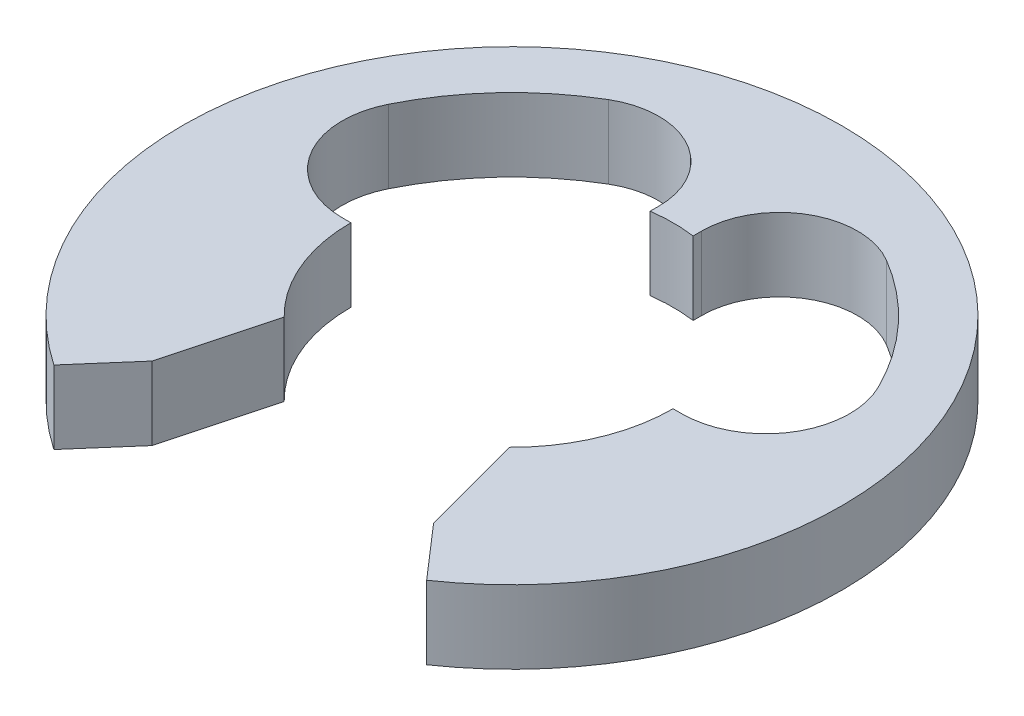
SolidWorks part; units mm, degrees
ref_plane "Plane1" through (0, 0, 0) normal (0, 0, 1) x (1, 0, 0)
ref_plane "Plane2" through (0, 0, 0) normal (0, 1, 0) x (1, 0, 0)
ref_plane "Plane3" through (0, 0, 0) normal (1, 0, 0) x (0, 0, -1)
extrude "Base-Extrude" add sketch "Sketch1" against normal blind 0.5
sketch "Sketch1" plane through (0, 0, 0) normal (0, 1, 0) x (1, 0, 0)
  line L0 (0, 0) -> (0, 100) construction
  line L1 (0.77, -0.7856) -> (0.9604, -1.4961)
  line L2 (0.9604, -1.4961) -> (1.2728, -1.8554)
  line L3 (0.1467, 1.0902) -> (0.1467, 1.1488)
  line L4 (1.1, 0) -> (1.1587, 0)
  line L5 (-1.1, 0) -> (-1.1587, 0)
  line L6 (-0.1467, 1.0902) -> (-0.1467, 1.1488)
  line L7 (-0.9604, -1.4961) -> (-1.2728, -1.8554)
  line L8 (-0.77, -0.7856) -> (-0.9604, -1.4961)
  arc A0 (1.2728, -1.8554) -> (-1.2728, -1.8554) centre (0, 0) ccw
  arc A1 (0.1467, 1.0902) -> (-0.1467, 1.0902) centre (0, 0) ccw
  arc A2 (1.6728, 0.8283) -> (0.9497, 1.607) centre (0, 0) ccw
  arc A3 (0.77, -0.7856) -> (1.1, 0) centre (0, 0) ccw
  arc A4 (0.1467, 1.1488) -> (0.9497, 1.607) centre (0.6789, 1.1488) cw
  arc A5 (1.1587, 0) -> (1.6728, 0.8283) centre (1.1587, 0.5737) ccw
  arc A6 (-1.1587, 0) -> (-1.6728, 0.8283) centre (-1.1587, 0.5737) cw
  arc A7 (-0.1467, 1.1488) -> (-0.9497, 1.607) centre (-0.6789, 1.1488) ccw
  arc A8 (-0.77, -0.7856) -> (-1.1, 0) centre (0, 0) cw
  arc A9 (-1.6728, 0.8283) -> (-0.9497, 1.607) centre (0, 0) cw
  dimension "D2" = 1.54
  dimension "_d3" = 4.5
  dimension "D5" = 3.7333
  dimension "_d" = 2.2
  dimension "D3" = 26
  dimension "D4" = 75
  dimension "D6" = 0.2933
  dimension "D7" = 0.0587
  dimension "D8" = 0.0587
  dimension "D9" = 1.7778
equation "\"D2@Sketch1\" = \"_d@Sketch1\"*0.7"
equation "\"D6@Sketch1\" = \"_d@Sketch1\"/7.5"
equation "\"D7@Sketch1\" = \"D6@Sketch1\"*0.2"
equation "\"D8@Sketch1\" = \"D7@Sketch1\""
equation "\"D5@Sketch1\" = (\"_d3@Sketch1\"-\"_d@Sketch1\")/1.5+\"_d@Sketch1\""
equation "\"D9@Sketch1\" = \"D5@Sketch1\"/2.1"
